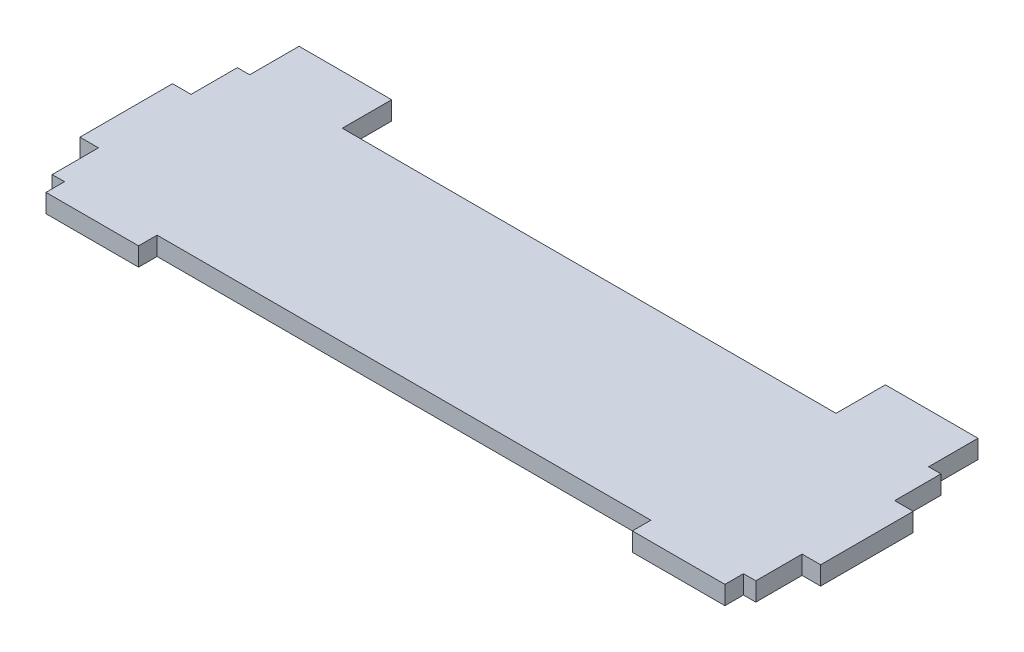
SolidWorks part; units mm, degrees
ref_plane "Front Plane" through (0, 0, 0) normal (0, 0, 1) x (1, 0, 0)
ref_plane "Top Plane" through (0, 0, 0) normal (0, 1, 0) x (1, 0, 0)
ref_plane "Right Plane" through (0, 0, 0) normal (1, 0, 0) x (0, 0, -1)
sketch "Sketch1" plane through (0, 0, 0) normal (0, 1, 0) x (1, 0, 0)
  line L9 (57, 15) -> (57, 7.5)
  line L10 (57, 7.5) -> (60, 7.5)
  line L15 (60, 7.5) -> (60, -7.5)
  line L16 (60, -7.5) -> (57, -7.5)
  line L21 (57, -7.5) -> (57, -15)
  line L23 (-57, -15) -> (-57, -7.5)
  line L24 (-57, -7.5) -> (-60, -7.5)
  line L25 (-60, -7.5) -> (-60, 7.5)
  line L26 (-60, 7.5) -> (-57, 7.5)
  line L27 (-57, 7.5) -> (-57, 15)
  line L28 (-57, 15) -> (-55, 15)
  line L33 (-55, 15) -> (-55, 23)
  line L34 (-55, 23) -> (-40, 23)
  line L39 (-40, 23) -> (-40, 15)
  line L40 (-40, 15) -> (40, 15)
  line L41 (40, 15) -> (40, 23)
  line L42 (40, 23) -> (55, 23)
  line L43 (55, 23) -> (55, 15)
  line L44 (55, 15) -> (57, 15)
  line L45 (-57, -15) -> (-55, -15)
  line L46 (-55, -15) -> (-55, -18)
  line L47 (-55, -18) -> (-40, -18)
  line L48 (-40, -18) -> (-40, -15)
  line L49 (-40, -15) -> (40, -15)
  line L50 (40, -15) -> (40, -18)
  line L51 (40, -18) -> (55, -18)
  line L52 (55, -18) -> (55, -15)
  line L53 (55, -15) -> (57, -15)
  point P0 (0, 0)
  point P17 (-57, 7.5)
  point P18 (-60, 7.5)
  point P19 (57, 7.5)
  point P20 (-57, 15)
  point P21 (57, 15)
  point P22 (57, -7.5)
  point P23 (60, 7.5)
  point P24 (60, -7.5)
  point P25 (-57, -7.5)
  point P26 (57, -15)
  point P27 (-57, -15)
  point P29 (-60, -7.5)
  point P31 (-40, 15)
  point P35 (-40, -15)
  point P36 (-55, 15)
  point P37 (55, 15)
  point P38 (-40, 23)
  point P39 (40, 23)
  point P40 (-55, 23)
  point P41 (55, 23)
  point P42 (40, 15)
  point P43 (40, -15)
  point P44 (55, -15)
  point P53 (0, 0)
  point P54 (0, 0)
  point P55 (0, 0)
  point P56 (0, 0)
  point P57 (0, 0)
  point P58 (0, 0)
  point P59 (0, 0)
  point P60 (0, 0)
  point P61 (0, 0)
  point P62 (0, 0)
  point P63 (0, 0)
  point P64 (-55, -15)
  point P65 (0, 0)
  point P66 (0, 0)
  point P67 (0, 0)
  point P68 (0, 0)
extrude "Boss-Extrude1" add sketch "Sketch1" along normal blind 3
